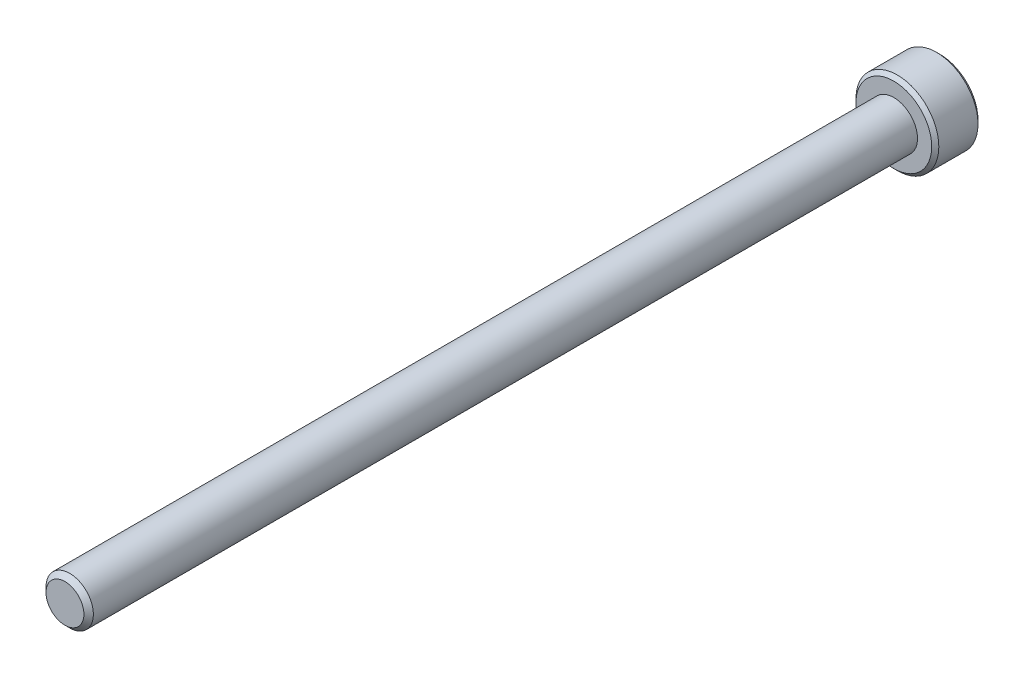
SolidWorks part; units mm, degrees
material "AISI 304"
ref_plane "前视基准面" through (0, 0, 0) normal (0, 0, 1) x (1, 0, 0)
ref_plane "上视基准面" through (0, 0, 0) normal (0, 1, 0) x (1, 0, 0)
ref_plane "右视基准面" through (0, 0, 0) normal (1, 0, 0) x (0, 0, -1)
sketch "草图1" plane through (0, 0, 0) normal (0, 0, 1) x (1, 0, 0)
  circle A0 centre (0, 0) radius 3.5
  dimension "D1" = 7
extrude "凸台-拉伸1" add sketch "草图1" along normal blind 3.91
sketch "草图2" plane through (0, 0, 3.91) normal (0, 0, 1) x (1, 0, 0)
  circle A0 centre (0, 0) radius 2
  dimension "D1" = 4
extrude "凸台-拉伸2" add sketch "草图2" along normal blind 70
sketch "草图3" plane through (0, 0, 0) normal (0, 0, -1) x (-1, 0, 0)
  line L1 (0, 1.7609) -> (-1.525, 0.8805)
  line L2 (-1.525, 0.8805) -> (-1.525, -0.8805)
  line L3 (-1.525, -0.8805) -> (0, -1.7609)
  line L4 (0, -1.7609) -> (1.525, -0.8805)
  line L5 (1.525, -0.8805) -> (1.525, 0.8805)
  line L6 (1.525, 0.8805) -> (0, 1.7609)
  circle A0 centre (0, 0) radius 1.525 construction
  dimension "D1" = 3.05
extrude "切除-拉伸1" cut sketch "草图3" against normal blind 2
chamfer "倒角1" distance 0.4 angle 45 1 edges at (2, 0, 73.91)
chamfer "倒角2" distance 0.3 angle 45 2 edges at (3.5, 0, 3.91) (3.5, 0, 0)
